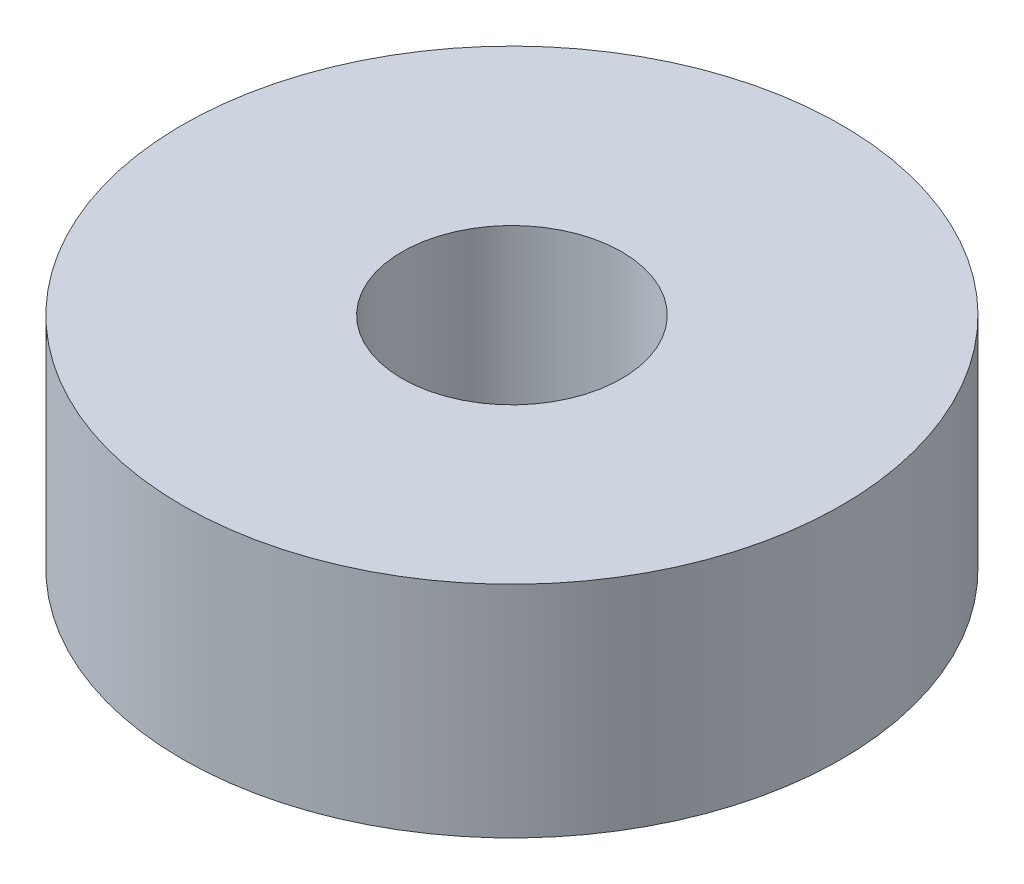
SolidWorks part; units mm, degrees
material "6061 Alloy"
ref_plane "Front Plane" through (0, 0, 0) normal (0, 0, 1) x (1, 0, 0)
ref_plane "Top Plane" through (0, 0, 0) normal (0, 1, 0) x (1, 0, 0)
ref_plane "Right Plane" through (0, 0, 0) normal (1, 0, 0) x (0, 0, -1)
sketch "Sketch1" plane through (0, 0, 0) normal (0, 1, 0) x (1, 0, 0)
  circle A0 centre (0, 0) radius 3.175
  circle A1 centre (0, 0) radius 9.525
  dimension "D1" = 6.35
  dimension "D2" = 19.05
extrude "Boss-Extrude1" add sketch "Sketch1" along normal mid plane 6.35
